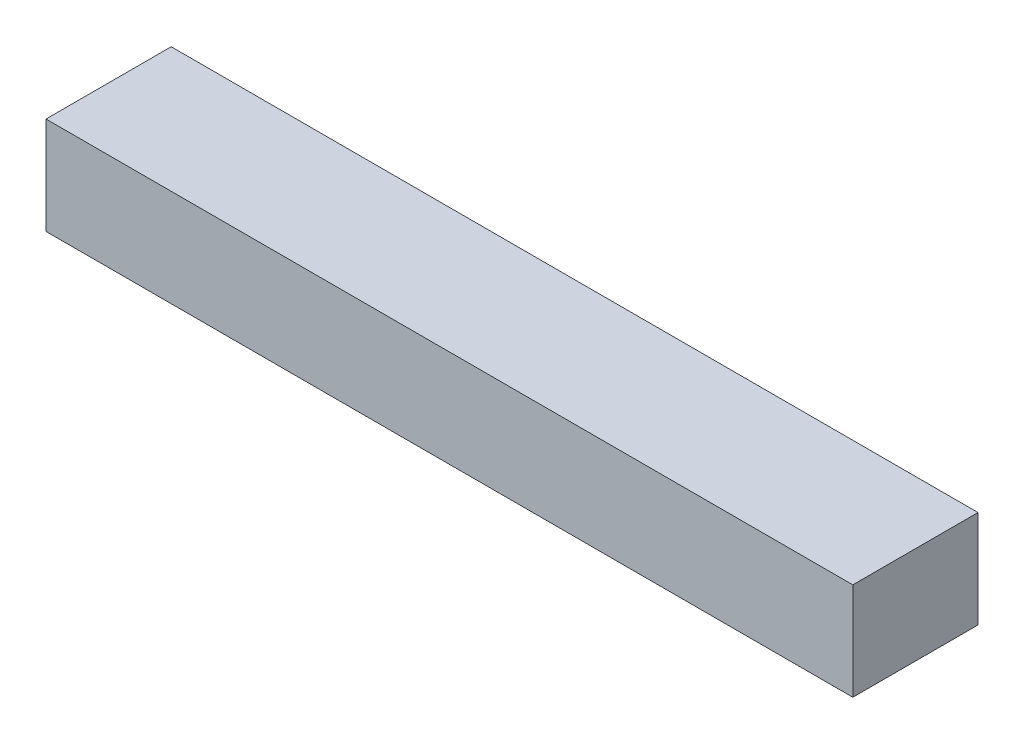
SolidWorks part; units mm, degrees
ref_plane "前视基准面" through (0, 0, 0) normal (0, 0, 1) x (1, 0, 0)
ref_plane "上视基准面" through (0, 0, 0) normal (0, 1, 0) x (1, 0, 0)
ref_plane "右视基准面" through (0, 0, 0) normal (1, 0, 0) x (0, 0, -1)
other "Configuration Table"
sketch "草图1" plane through (0, 0, 0) normal (0, 0, 1) x (1, 0, 0)
  line L1 (-58, -7) -> (58, -7)
  line L2 (-58, -7) -> (-58, 7)
  line L3 (-58, 7) -> (58, 7)
  line L4 (58, -7) -> (58, 7)
extrude "凸台-拉伸1" add sketch "草图1" against normal blind 18
